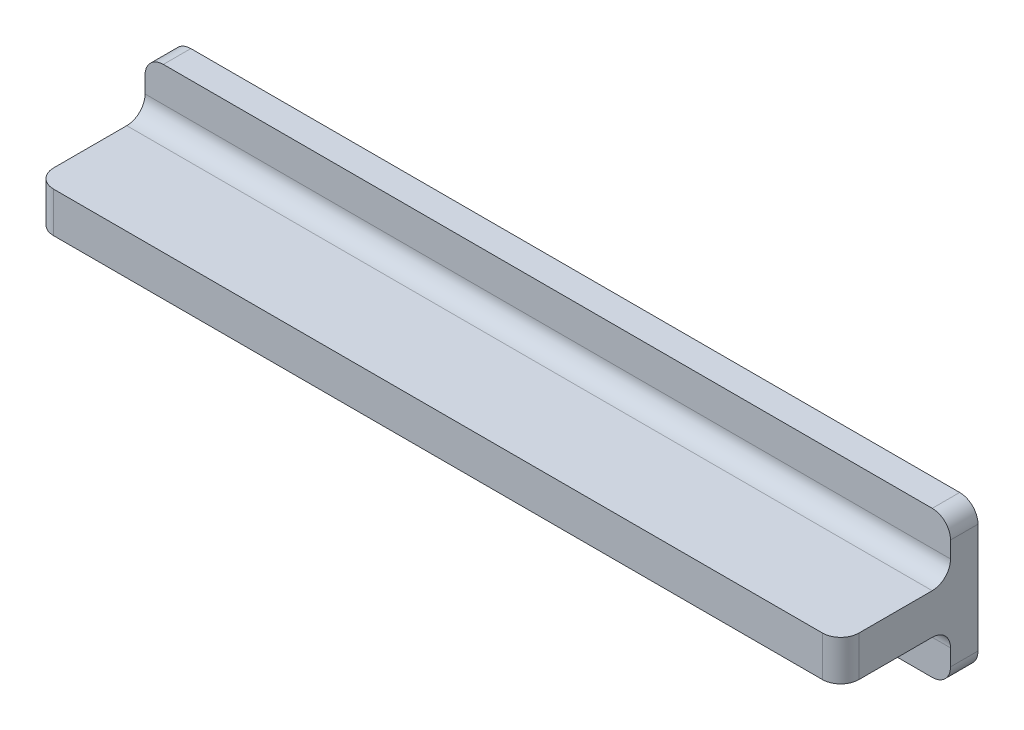
SolidWorks part; units mm, degrees
material "ABS"
ref_plane "X-Y Datum" through (0, 0, 0) normal (0, 0, 1) x (1, 0, 0)
ref_plane "X-Z Datum" through (0, 0, 0) normal (0, 1, 0) x (1, 0, 0)
ref_plane "Y-Z Datum" through (0, 0, 0) normal (1, 0, 0) x (0, 0, -1)
sketch "Sketch1" plane through (0, 0, 0) normal (0, 0, 1) x (1, 0, 0)
  line L1 (-69.85, 12.7) -> (69.85, 12.7)
  line L2 (-69.85, 12.7) -> (-69.85, -12.7)
  line L3 (-69.85, -12.7) -> (69.85, -12.7)
  line L4 (69.85, 12.7) -> (69.85, -12.7)
  line L5 (-69.85, 12.7) -> (69.85, -12.7) construction
  line L6 (-69.85, -12.7) -> (69.85, 12.7) construction
  point P0 (0, 0)
  dimension "D1" = 139.7
  dimension "D2" = 25.4
extrude "Boss-Extrude1" add sketch "Sketch1" along normal blind 4.7625
sketch "Sketch2" plane through (0, 0, 4.7625) normal (0, 0, 1) x (1, 0, 0)
  line L0 (69.85, -12.7) -> (69.85, 12.7) construction
  line L1 (-69.85, 3.5) -> (69.85, 3.5)
  line L2 (-69.85, 3.5) -> (-69.85, -3.5)
  line L3 (-69.85, -3.5) -> (69.85, -3.5)
  line L4 (69.85, 3.5) -> (69.85, -3.5)
  line L5 (-69.85, 3.5) -> (69.85, -3.5) construction
  line L6 (-69.85, -3.5) -> (69.85, 3.5) construction
  point P0 (0, 0)
  dimension "D1" = 7
extrude "Boss-Extrude2" add sketch "Sketch2" along normal blind 19.05
fillet "Fillet1" radius 3.175 8 edges at (0, 3.5, 4.7625) (0, -3.5, 4.7625) (-69.85, 0, 23.8125) (69.85, 0, 23.8125) (69.85, 12.7, 2.3813) (69.85, -12.7, 2.3813) (-69.85, 12.7, 2.3813) (-69.85, -12.7, 2.3813)
